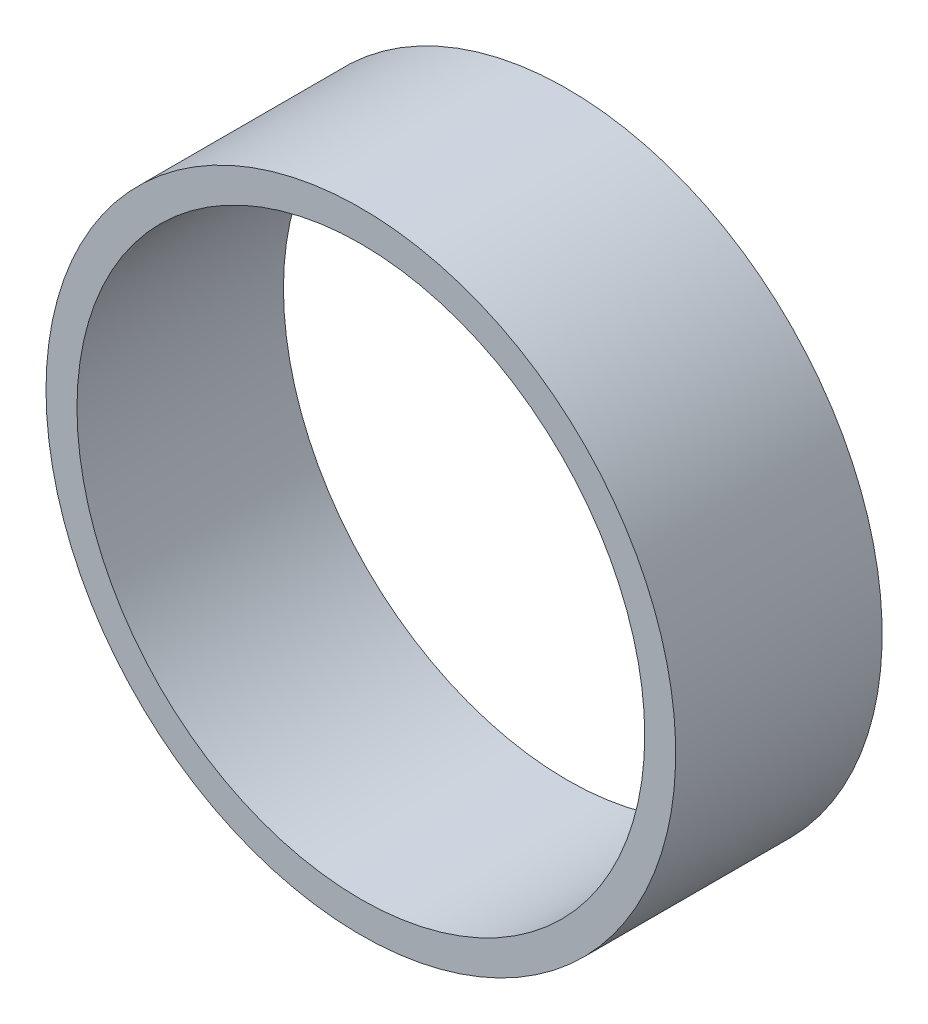
SolidWorks part; units mm, degrees
material "1.0050 (E295)"
ref_plane "Front Plane" through (0, 0, 0) normal (0, 0, 1) x (1, 0, 0)
ref_plane "Top Plane" through (0, 0, 0) normal (0, 1, 0) x (1, 0, 0)
ref_plane "Right Plane" through (0, 0, 0) normal (1, 0, 0) x (0, 0, -1)
sketch "Sketch1" plane through (0, 0, 0) normal (0, 0, 1) x (1, 0, 0)
  circle A0 centre (0, 0) radius 27.5
  circle A1 centre (0, 0) radius 30.5
  dimension "D1" = 55
  dimension "D2" = 61
extrude "Boss-Extrude1" add sketch "Sketch1" along normal blind 20
